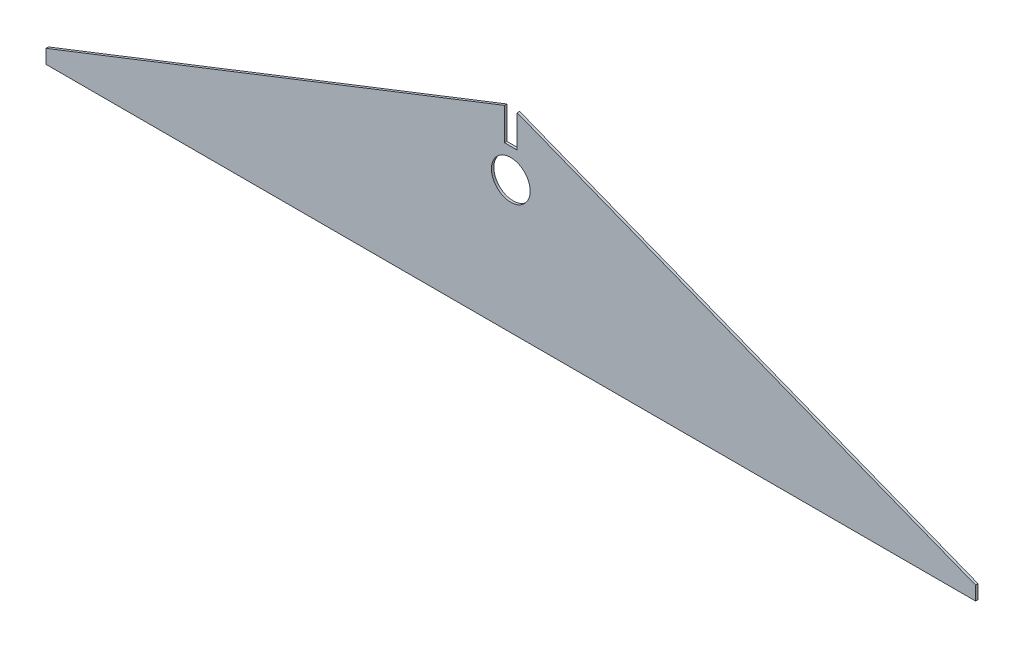
SolidWorks part; units mm, degrees
ref_plane "Front Plane" through (0, 0, 0) normal (0, 0, 1) x (1, 0, 0)
ref_plane "Top Plane" through (0, 0, 0) normal (0, 1, 0) x (1, 0, 0)
ref_plane "Right Plane" through (0, 0, 0) normal (1, 0, 0) x (0, 0, -1)
sketch "Sketch1" plane through (0, 0, 0) normal (0, 0, 1) x (1, 0, 0)
  line L0 (0, 0) -> (3657.6, 0)
  line L1 (0, 0) -> (-3657.6, 0)
  line L2 (-3657.6, 0) -> (-3657.6, 109.22)
  line L3 (3657.6, 0) -> (3657.6, 109.22)
  line L14 (-50.8, 1524) -> (-3657.6, 109.22)
  line L15 (50.8, 1524) -> (3657.6, 109.22)
  line L16 (-50.8, 1524) -> (-50.8, 1270)
  line L17 (-50.8, 1270) -> (50.8, 1270)
  line L18 (50.8, 1270) -> (50.8, 1524)
  circle A1 centre (0, 1041.4) radius 152.4
extrude "Boss-Extrude1" add sketch "Sketch1" along normal blind 19.05
